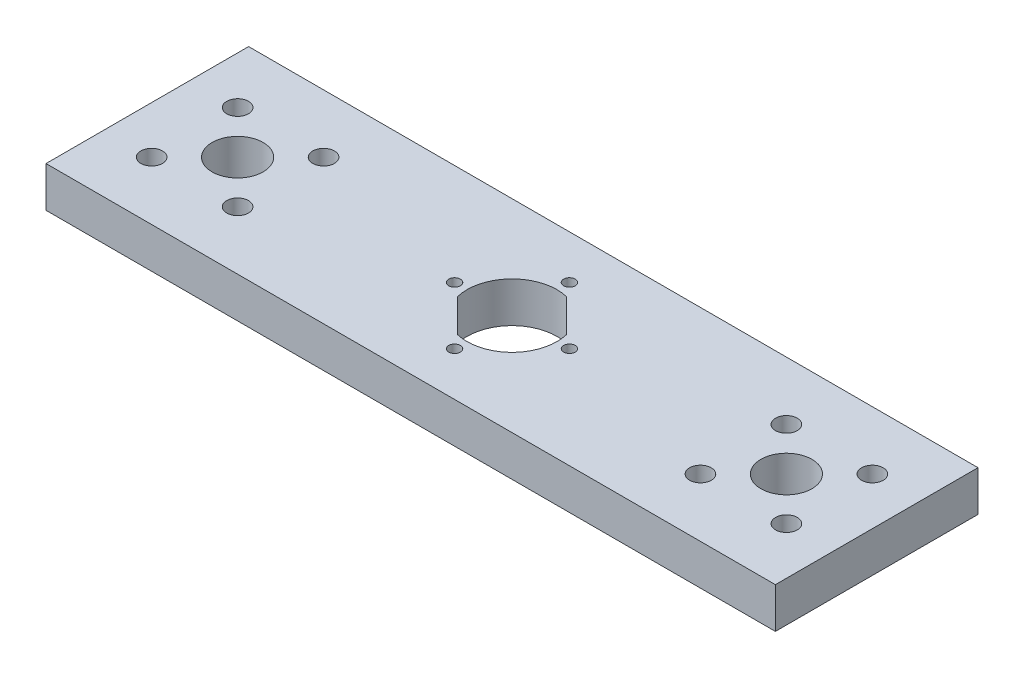
SolidWorks part; units mm, degrees
ref_plane "Front Plane" through (0, 0, 0) normal (0, 0, 1) x (1, 0, 0)
ref_plane "Top Plane" through (0, 0, 0) normal (0, 1, 0) x (1, 0, 0)
ref_plane "Right Plane" through (0, 0, 0) normal (1, 0, 0) x (0, 0, -1)
sketch "Sketch2" plane through (0, 0, 0) normal (0, 1, 0) x (1, 0, 0)
  line L0 (6.7979, 1.7581) -> (1.7581, 6.7979)
  line L1 (-57.15, -15.875) -> (57.15, -15.875)
  line L2 (-57.15, -15.875) -> (-57.15, 15.875)
  line L3 (-57.15, 15.875) -> (57.15, 15.875)
  line L4 (57.15, -15.875) -> (57.15, 15.875)
  line L5 (-57.15, -15.875) -> (57.15, 15.875) construction
  line L6 (-57.15, 15.875) -> (57.15, -15.875) construction
  line L7 (-6.7979, -1.7581) -> (-1.7581, -6.7979)
  line L16 (0, 9) -> (0, -9) construction
  line L17 (-9, 0) -> (9, 0) construction
  line L18 (-57.15, 0) -> (57.15, 0) construction
  line L19 (0, 15.875) -> (0, -15.875)
  line L20 (-43, 0) -> (-36.2648, 6.7352) construction
  line L21 (-43, 0) -> (-43, 15.875) construction
  line L22 (-43, 0) -> (-49.7352, 6.7352) construction
  line L23 (-43, 0) -> (-36.2648, -6.7352) construction
  line L24 (-43, 0) -> (-49.7352, -6.7352) construction
  line L25 (43, 0) -> (49.7352, -6.7352) construction
  line L26 (43, 0) -> (36.2648, -6.7352) construction
  line L27 (43, 0) -> (36.2648, 6.7352) construction
  line L28 (43, 0) -> (49.7352, 6.7352) construction
  arc A8 (6.8508, 1.6639) -> (6.7979, 1.7581) centre (6.6565, 1.6167) ccw
  arc A9 (1.7581, 6.7979) -> (1.6639, 6.8508) centre (1.6167, 6.6565) ccw
  arc A10 (-6.8508, -1.6639) -> (-6.7979, -1.7581) centre (-6.6565, -1.6167) ccw
  arc A11 (1.6639, 6.8508) -> (-6.8508, -1.6639) centre (0, 0) ccw
  arc A12 (-1.7581, -6.7979) -> (-1.6639, -6.8508) centre (-1.6167, -6.6565) ccw
  arc A13 (-1.6639, -6.8508) -> (6.8508, 1.6639) centre (0, 0) ccw
  circle A14 centre (-9, 0) radius 0.9115
  circle A15 centre (0, -9) radius 0.9115
  circle A16 centre (9, 0) radius 0.9115
  circle A17 centre (0, 9) radius 0.9115
  circle A22 centre (-43, 0) radius 4
  circle A23 centre (43, 0) radius 4
  circle A24 centre (-36.2648, 6.7352) radius 1.7
  circle A25 centre (-49.7352, 6.7352) radius 1.7
  circle A26 centre (-36.2648, -6.7352) radius 1.7
  circle A27 centre (-49.7352, -6.7352) radius 1.7
  circle A28 centre (49.7352, -6.7352) radius 1.7
  circle A29 centre (36.2648, -6.7352) radius 1.7
  circle A30 centre (36.2648, 6.7352) radius 1.7
  circle A31 centre (49.7352, 6.7352) radius 1.7
  point P0 (0, 0)
  dimension "D5" = 1.823
  dimension "D6" = 1.823
  dimension "D7" = 1.823
  dimension "D8" = 1.823
  dimension "D9" = 8
  dimension "D10" = 8
  dimension "D13" = 3.4
  dimension "D1" = 114.3
  dimension "D2" = 31.75
  dimension "D3" = 18
  dimension "D4" = 18
  dimension "D11" = 43
  dimension "D12" = 43
  dimension "D14" = 9.525
  dimension "D15" = 45
  dimension "D16" = 9.525
extrude "Boss-Extrude1" add sketch "Sketch2" along normal blind 6.35
equation "\"Motor Center Dist\" = 43mm"
equation "\"D12@Sketch2\"=\"Motor Center Dist\""
equation "\"D11@Sketch2\"=\"Motor Center Dist\""
